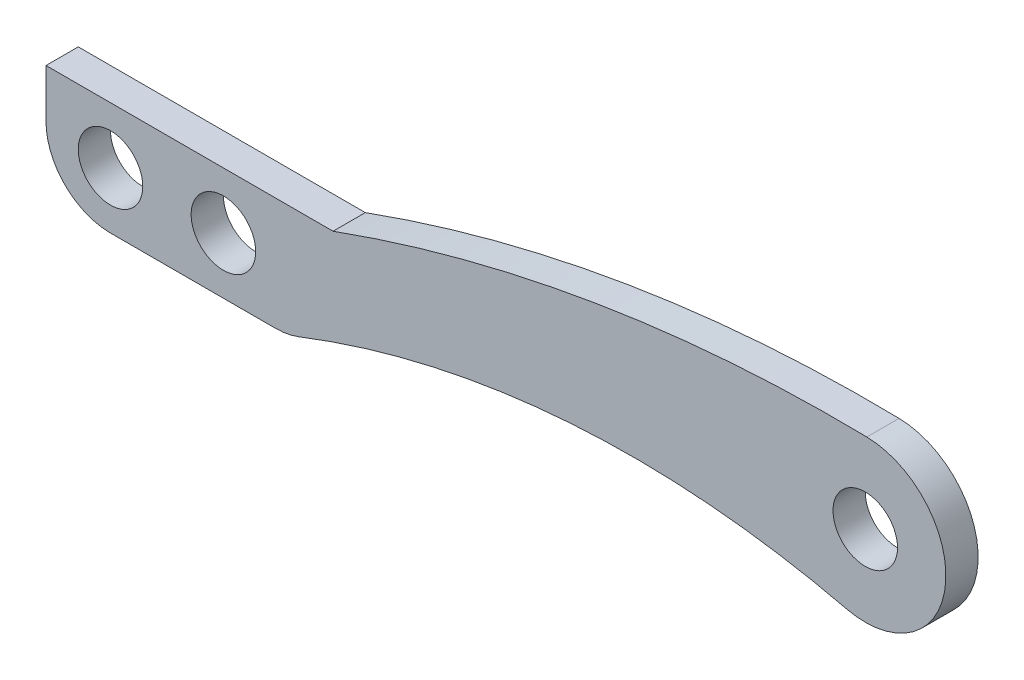
SolidWorks part; units mm, degrees
ref_plane "Front Plane" through (0, 0, 0) normal (0, 0, 1) x (1, 0, 0)
ref_plane "Top Plane" through (0, 0, 0) normal (0, 1, 0) x (1, 0, 0)
ref_plane "Right Plane" through (0, 0, 0) normal (1, 0, 0) x (0, 0, -1)
sketch "Sketch1" plane through (0, 0, 0) normal (0, 0, 1) x (1, 0, 0)
  line L0 (-74.8928, 0) -> (42.3913, 0) construction
  line L1 (-36, 3.5) -> (-33, 3.5)
  line L2 (-50.8005, -3.5) -> (-35.8005, -3.5)
  line L3 (-50.8005, -3.5) -> (-50.8005, 3.5)
  line L4 (-50.8005, 3.5) -> (-36, 3.5)
  arc A0 (-1.1581, -0.8643) -> (0.0962, 8.9991) centre (-0.001, 4) ccw
  circle A1 centre (-0.001, 4) radius 2
  circle A2 centre (-46.8005, 0) radius 2
  circle A3 centre (-39.8005, 0) radius 2
  arc A4 (-1.1581, -0.8643) -> (-35.8005, -3.5) centre (-14.3576, -56.3558) ccw
  arc A5 (-33, 3.5) -> (0.0962, 8.9991) centre (-1.6856, -82.6218) cw
  dimension "D1" = 10
  dimension "D2" = 4
  dimension "D9" = 4
  dimension "D3" = 7
  dimension "D4" = 40
  dimension "D5" = 7
  dimension "D6" = 15
  dimension "D7" = 4
  dimension "D8" = 3
extrude "Boss-Extrude1" add sketch "Sketch1" along normal blind 2
fillet "Fillet1" radius 4 2 edges at (-35.8005, -3.5, 1) (-50.8005, -3.5, 1)
